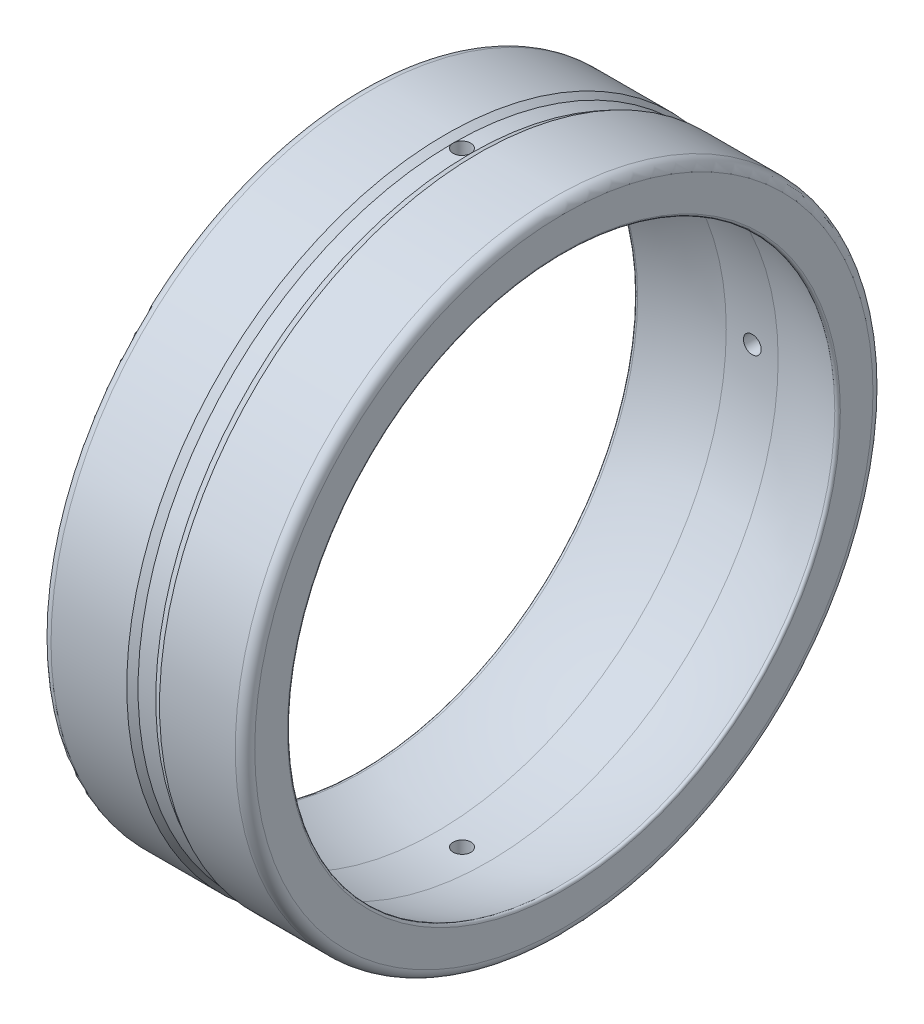
SolidWorks part; units mm, degrees
material "Liga de aço"
ref_plane "Plano frontal" through (0, 0, 0) normal (0, 0, 1) x (1, 0, 0)
ref_plane "Plano superior" through (0, 0, 0) normal (0, 1, 0) x (1, 0, 0)
ref_plane "Plano direito" through (0, 0, 0) normal (1, 0, 0) x (0, 0, -1)
sketch "Esboço1" plane through (0, 0, 0) normal (0, 0, 1) x (1, 0, 0)
  line L0 (0, 36) -> (0, 0)
  line L1 (0, 0) -> (23, 0)
  line L2 (23, 0) -> (23, 36)
  line L3 (23, 36) -> (13.35, 36)
  line L4 (13.35, 36) -> (12.5, 35.575)
  line L5 (12.5, 35.575) -> (10.5, 35.575)
  line L6 (10.5, 35.575) -> (9.65, 36)
  line L7 (9.65, 36) -> (0, 36)
  line L8 (0, 0) -> (23, 0) construction
revolve "Revolução1" add sketch "Esboço1" angle 360 about L8
sketch "Esboço2" plane through (0, 0, 0) normal (0, 0, 1) x (1, 0, 0)
  line L0 (0, 31.2161) -> (0, 0)
  line L1 (0, 0) -> (23, 0)
  line L2 (23, 0) -> (23, 31.2161)
  line L3 (-0.0013, 0) -> (23.0013, 0) construction
  arc A0 (23, 31.2161) -> (22.6314, 30.9575) centre (22.725, 31.2161) cw
  arc A1 (22.6314, 30.9575) -> (14.4302, 32.7662) centre (11.6316, 0.5781) ccw
  arc A2 (14.4302, 32.7662) -> (8.5698, 32.7662) centre (11.5, -317.2215) ccw
  arc A3 (8.5698, 32.7662) -> (0.3686, 30.9575) centre (11.3684, 0.5781) ccw
  arc A4 (0.3686, 30.9575) -> (0, 31.2161) centre (0.275, 31.2161) cw
revolve "Corte-Revolução1" cut sketch "Esboço2" angle 360 about L3
ref_plane "Plano1" through (0, 32.7632, 0) normal (0, -1, 0) x (-1, 0, 0)
hole_wizard "Furo de diâmetro Ø2.0 (2)1" positions "Esboço4" profile "Esboço3" hole size "Ø2.0" standard "Ansi Metric"
sketch "Esboço4" plane through (0, 32.7632, 0) normal (0, -1, 0) x (-1, 0, 0)
  point P0 (-11.5, 0)
sketch "Esboço3" plane through (11.5, 32.7632, 0) normal (1, 0, 0) x (0, 0, -1)
  line L0 (0, 0) -> (0, 3.2368)
  line L1 (0, 3.2368) -> (1, 3.2368)
  line L2 (1, 3.2368) -> (1, 0)
  line L5 (1, 0) -> (0, 0)
  line L11 (0, -6.35) -> (0, 107.95) construction
  dimension "Thru Hole Dia." = 2
  dimension "Thru Hole Depth" = 3.2368
ref_plane "Plano2" through (0, 0, -32.7632) normal (0, 0, 1) x (1, 0, 0)
hole_wizard "Furo de diâmetro Ø2.0 (2)2" positions "Esboço6" profile "Esboço5" hole size "Ø2.0" standard "Ansi Metric"
sketch "Esboço6" plane through (0, 0, -32.7632) normal (0, 0, 1) x (1, 0, 0)
  point P0 (11.5, 0)
sketch "Esboço5" plane through (11.5, 0, -32.7632) normal (1, 0, 0) x (0, -1, 0)
  line L0 (0, 0) -> (0, 3.2368)
  line L1 (0, 3.2368) -> (1, 3.2368)
  line L2 (1, 3.2368) -> (1, 0)
  line L5 (1, 0) -> (0, 0)
  line L11 (0, -6.35) -> (0, 107.95) construction
  dimension "Thru Hole Dia." = 2
  dimension "Thru Hole Depth" = 3.2368
ref_plane "Plano3" through (0, -32.7632, 0) normal (0, 1, 0) x (1, 0, 0)
hole_wizard "Furo de diâmetro Ø2.0 (2)3" positions "Esboço8" profile "Esboço7" hole size "Ø2.0" standard "Ansi Metric"
sketch "Esboço8" plane through (0, -32.7632, 0) normal (0, 1, 0) x (1, 0, 0)
  point P0 (11.5, 0)
sketch "Esboço7" plane through (11.5, -32.7632, 0) normal (1, 0, 0) x (0, 0, 1)
  line L0 (0, 0) -> (0, 3.2368)
  line L1 (0, 3.2368) -> (1, 3.2368)
  line L2 (1, 3.2368) -> (1, 0)
  line L5 (1, 0) -> (0, 0)
  line L11 (0, -6.35) -> (0, 107.95) construction
  dimension "Thru Hole Dia." = 2
  dimension "Thru Hole Depth" = 3.2368
fillet "Filete1" radius 1.1 2 edges at (0, 0, -36) (23, 0, -36)
